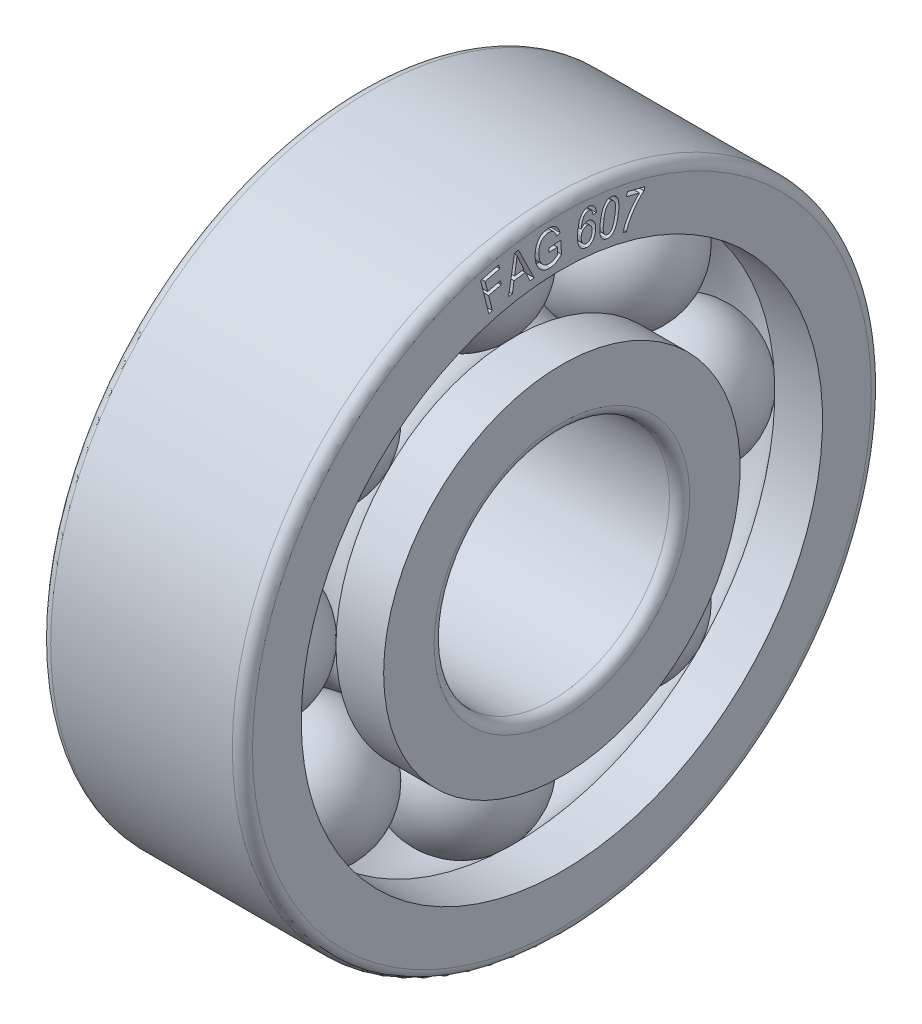
SolidWorks part; units mm, degrees
ref_plane "Alzado" through (0, 0, 0) normal (0, 0, 1) x (1, 0, 0)
ref_plane "Planta" through (0, 0, 0) normal (0, 1, 0) x (1, 0, 0)
ref_plane "Vista lateral" through (0, 0, 0) normal (1, 0, 0) x (0, 0, -1)
sketch "Sketch1" plane through (0, 0, 0) normal (0, 0, 1) x (1, 0, 0)
  line L0 (0, 0) -> (29.9021, 0) construction
  line L1 (0, 7.75) -> (1.4191, 7.75)
  line L2 (0, 9.5) -> (6, 9.5)
  line L3 (0, 9.5) -> (0, 7.75)
  line L4 (0, 3.5) -> (6, 3.5)
  line L5 (6, 9.5) -> (6, 7.75)
  line L6 (0, 5.3) -> (1.4191, 5.3)
  line L7 (0, 5.3) -> (0, 3.5)
  line L8 (6, 5.3) -> (6, 3.5)
  line L9 (0, 7.75) -> (0, 5.3) construction
  line L10 (0, 6.525) -> (6, 6.525) construction
  line L11 (4.5809, 5.3) -> (6, 5.3)
  line L12 (4.5809, 7.75) -> (6, 7.75)
  arc A0 (1.4191, 5.3) -> (4.5809, 5.3) centre (3, 6.525) ccw
  arc A1 (4.5809, 7.75) -> (1.4191, 7.75) centre (3, 6.525) ccw
  dimension "D6" = 4
  dimension "D1" = 6
  dimension "D2" = 3.5
  dimension "D3" = 9.5
  dimension "D4" = 7.75
  dimension "D5" = 5.3
revolve "Revolve1" add sketch "Sketch1" angle 360 about L0
fillet "Fillet1" radius 0.3 2 edges at (0, 0, 9.5) (6, 0, 9.5)
fillet "Fillet2" radius 0.3 2 edges at (0, 0, 3.5) (6, 0, 3.5)
sketch "Sketch2" plane through (0, 0, 0) normal (0, 0, 1) x (1, 0, 0)
  line L0 (3, 8.525) -> (3, 4.525)
  arc A0 (3, 8.525) -> (3, 4.525) centre (3, 6.525) ccw
  arc A1 (4.5809, 7.75) -> (1.4191, 7.75) centre (3, 6.525) ccw construction
revolve "Revolve2" add sketch "Sketch2" angle 360 about L0
pattern_circular "CirPattern2" count 8 over 360 about axis through (0, 0, 0) along (1, 0, 0) of bodies 103
sketch "Sketch4" plane through (6, 0, 0) normal (1, 0, 0) x (0, 0, -1)
  arc A0 (-2.7249, 7.5216) -> (2.7249, 7.5216) centre (0, 0) cw construction
  circle A1 centre (0, 0) radius 7.75 construction
  text T0 "FAG 607" font "Arial Narrow" height 1
  dimension "D1" = 0.25
extrude "Cut-Extrude1" cut sketch "Sketch4" against normal blind 0.3
